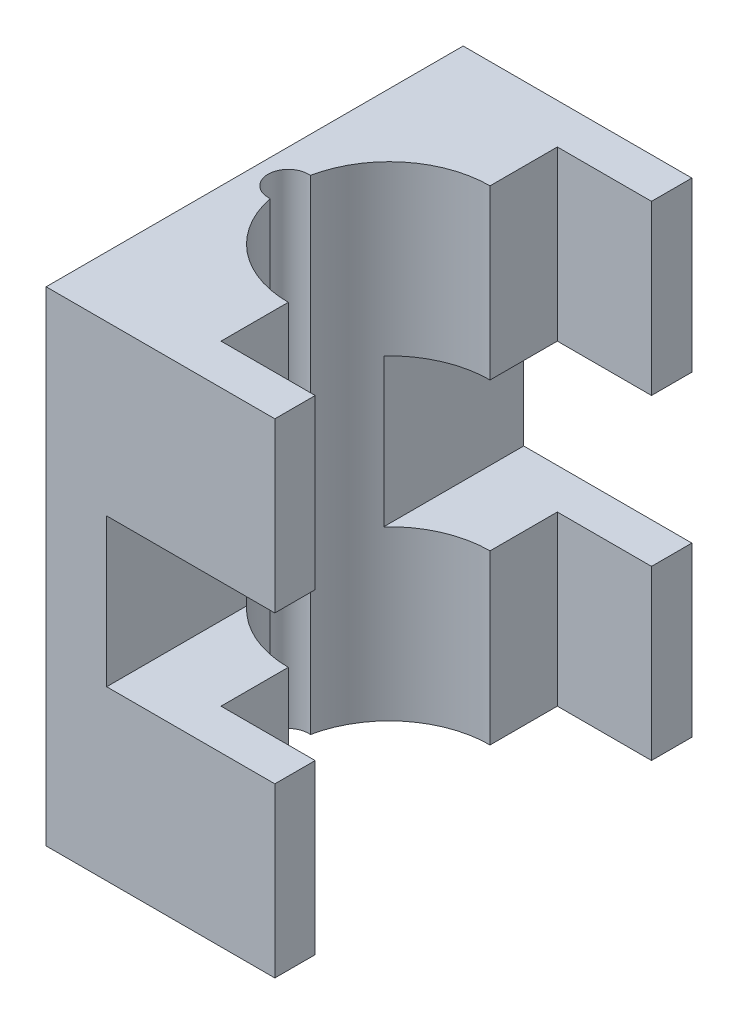
SolidWorks part; units mm, degrees
ref_plane "Front Plane" through (0, 0, 0) normal (0, 0, 1) x (1, 0, 0)
ref_plane "Top Plane" through (0, 0, 0) normal (0, 1, 0) x (1, 0, 0)
ref_plane "Right Plane" through (0, 0, 0) normal (1, 0, 0) x (0, 0, -1)
sketch "Sketch1" plane through (0, 0, 0) normal (0, 1, 0) x (1, 0, 0)
  line L0 (0, 0) -> (-15, 0) construction
  line L1 (20, 25) -> (0, 25)
  line L2 (20, -31) -> (-20, -31)
  line L3 (20, -31) -> (20, 31)
  line L4 (20, 31) -> (-20, 31)
  line L5 (-20, -31) -> (-20, 31)
  line L6 (20, -31) -> (-20, 31) construction
  line L7 (20, 31) -> (-20, -31) construction
  line L8 (0, 25) -> (0, -25)
  line L9 (0, -25) -> (20, -25)
  line L10 (14, -31) -> (14, -25)
  line L11 (14, 25) -> (14, 31)
  circle A0 centre (0, 0) radius 15
  circle A1 centre (-15, 0) radius 3
  dimension "D1" = 30
  dimension "D3" = 6
  dimension "D2" = 15
  dimension "D4" = 40
  dimension "D5" = 20
  dimension "D6" = 50
  dimension "D7" = 62
  dimension "D8" = 25
  dimension "D9" = 6
extrude "Boss-Extrude1" add sketch "Sketch1" along normal blind 25 contours A1 A0 L8 L1 L3 L4 L5 L2 L9
sketch "Sketch2" plane through (0, 25, 0) normal (0, 1, 0) x (1, 0, 0)
  line L0 (0, 0) -> (-15, 0) construction
  line L1 (-20, -31) -> (-20, 31)
  line L2 (-20, 31) -> (-11, 31)
  line L3 (14, 31) -> (-20, 31) construction
  line L4 (-11, 31) -> (-11, 10.198)
  line L5 (-20, -31) -> (-11, -31)
  line L6 (14, -31) -> (-20, -31) construction
  line L7 (-11, -31) -> (-11, -10.198)
  circle A0 centre (0, 0) radius 15
  circle A1 centre (-15, 0) radius 3
  arc M5 (-14.7, -2.985) -> (-14.7, 2.985) centre (-15, 0) cw
  arc M6 (-14.7, 2.985) -> (0, 15) centre (0, 0) cw
  line M10 (14, 31) -> (-20, 31)
  line M11 (-20, 31) -> (-20, -31)
  line M12 (-20, -31) -> (14, -31)
  arc M16 (0, -15) -> (-14.7, -2.985) centre (0, 0) cw
  dimension "D1" = 6
  dimension "D2" = 15
  dimension "D3" = 9
extrude "Boss-Extrude2" add sketch "Sketch2" along normal blind 22 contours L7 L4 M12 M16 M5 M6 M10 M11
ref_plane "Plane1" through (0, 36, 0) normal (0, 1, 0) x (1, 0, 0)
mirror "Mirror1" about plane through (0, 36, 0) normal (0, 1, 0) of "Boss-Extrude1"
